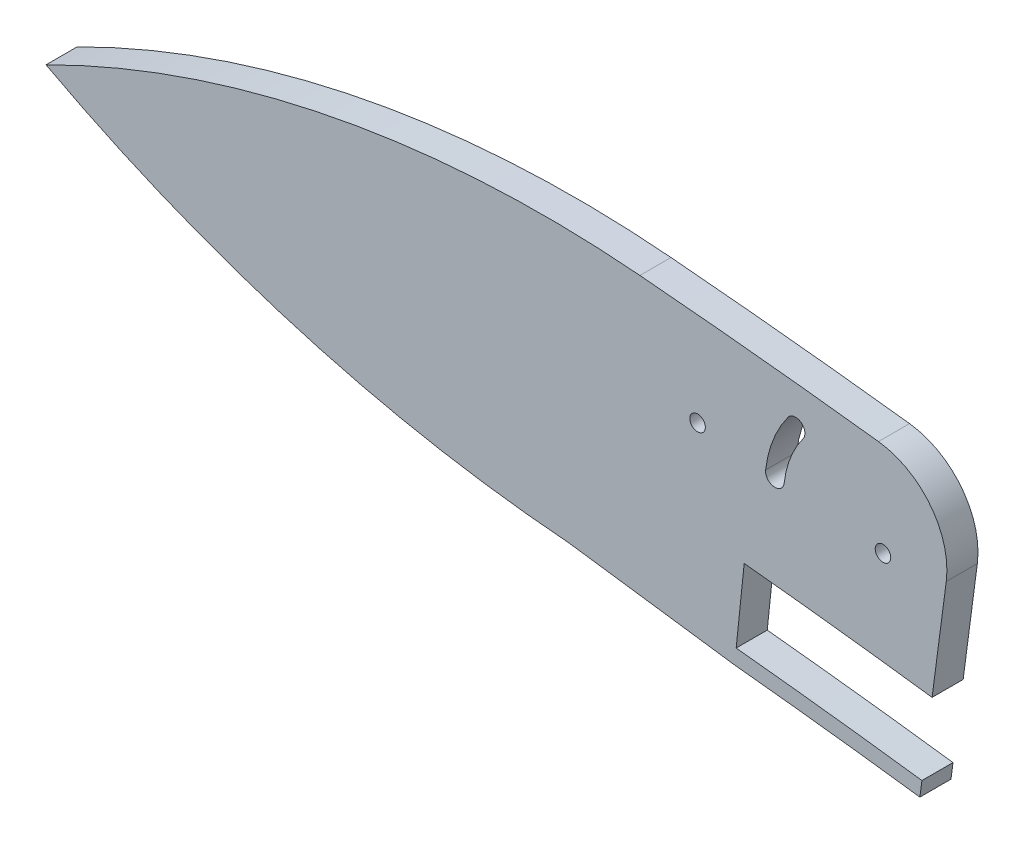
SolidWorks part; units mm, degrees
ref_plane "Přední rovina" through (0, 0, 0) normal (0, 0, 1) x (1, 0, 0)
ref_plane "Horní rovina" through (0, 0, 0) normal (0, 1, 0) x (1, 0, 0)
ref_plane "Pravá rovina" through (0, 0, 0) normal (1, 0, 0) x (0, 0, -1)
sketch "Skica1" plane through (0, 0, 0) normal (0, 0, 1) x (1, 0, 0)
  line L0 (59.8665, -4) -> (57.2058, -23.8222) construction
  line L1 (0, 0) -> (0, -20) construction
  arc A0 (0, 0) -> (59.8665, -4) centre (0, -450) cw construction
  arc A1 (0, -20) -> (57.2058, -23.8222) centre (0, -450) cw construction
  dimension "D1" = 450
  dimension "D2" = 20
  dimension "D3" = 60
sketch "Skica2" plane through (0, 0, 0) normal (0, 0, 1) x (1, 0, 0)
  line L0 (0, 0) -> (0, -20) construction
  line L1 (59.8665, -4) -> (57.2058, -23.8222) construction
  line L2 (58.5689, -5.845) -> (56.281, -23.1948)
  arc A2 (59.6004, -5.9822) -> (0, -2) centre (0, -450) ccw
  arc A3 (58.5689, -5.845) -> (38.2052, -3.632) centre (0, -450) ccw
  arc A4 (0, -11) -> (38.2052, -3.632) centre (32.1148, -74.7883) cw
  arc A5 (57.2723, -23.3267) -> (0, -19.5) centre (0, -450) ccw
  arc A6 (56.281, -23.1948) -> (33.6115, -20.8141) centre (0, -450) ccw
  arc A7 (33.6115, -20.8141) -> (0, -11) centre (40.2963, 64.5435) cw
  dimension "D3" = 11
  dimension "D4" = 1
  dimension "D1" = 2
  dimension "D2" = 0.5
extrude "Přidat vysunutím1" add sketch "Skica2" along normal mid plane 2
sketch "Skica3" plane through (0, 0, 1) normal (0, 0, 1) x (1, 0, 0)
  line L0 (59.8665, -4) -> (57.2058, -23.8222) construction
  arc A0 (53.8429, -11.2917) -> (41.9135, -9.9918) centre (0, -450) ccw construction
  arc A1 (59.8665, -4) -> (0, 0) centre (0, -450) ccw construction
  circle A2 centre (41.9135, -9.9918) radius 0.5
  circle A3 centre (53.8429, -11.2917) radius 0.5
  arc A4 (46.8885, -10.4941) -> (48.2191, -7.1237) centre (53.8429, -11.2917) cw construction
  arc A5 (47.737, -6.7665) -> (46.2924, -10.4257) centre (53.8429, -11.2917) ccw
  arc A6 (48.7011, -7.481) -> (47.4846, -10.5624) centre (53.8429, -11.2917) ccw
  arc A7 (48.7011, -7.481) -> (47.737, -6.7665) centre (48.2191, -7.1237) ccw
  arc A8 (46.2924, -10.4257) -> (47.4846, -10.5624) centre (46.8885, -10.4941) ccw
  point P10 (47.3319, -8.7213)
  dimension "D1" = 8
  dimension "D2" = 1
  dimension "D3" = 1
  dimension "D4" = 12
  dimension "D5" = 1.2
  dimension "D6" = 30
  dimension "D8" = 5
  dimension "D7" = 7
extrude "Odebrat vysunutím1" cut sketch "Skica3" against normal through all
sketch "Skica4" plane through (0, 0, 1) normal (0, 0, 1) x (1, 0, 0)
  line L0 (56.281, -23.1948) -> (58.5689, -5.845) construction
  line L1 (44.3467, -21.7902) -> (44.9133, -16.3195)
  arc A1 (57.0001, -17.742) -> (44.9133, -16.3195) centre (0, -450) ccw
  arc A2 (57.2058, -23.8222) -> (0, -20) centre (0, -450) ccw construction
  arc A3 (56.281, -23.1948) -> (33.6115, -20.8141) centre (0, -450) ccw construction
  dimension "D1" = 6
  dimension "D3" = 13
extrude "Odebrat vysunutím2" cut sketch "Skica4" against normal through all and the other way through all
sketch "Skica5" plane through (0, 0, 0) normal (0, 0, 1) x (1, 0, 0)
  line L0 (33.6115, -20.8141) -> (44.2952, -22.2876)
  line L1 (44.3982, -21.2929) -> (44.3467, -21.7902)
  line L2 (44.9133, -16.3195) -> (44.3467, -21.7902) construction
  line L3 (56.3464, -22.6991) -> (56.2157, -23.6905)
  line L6 (57.0001, -17.742) -> (58.5689, -5.845) construction
  arc A0 (57.2058, -23.8222) -> (0, -20) centre (0, -450) ccw construction
  arc A1 (56.2157, -23.6905) -> (44.2952, -22.2876) centre (0, -450) ccw
  arc A2 (56.3464, -22.6991) -> (44.3982, -21.2929) centre (0, -450) ccw
  arc A3 (57.3388, -22.8311) -> (0, -19) centre (0, -450) ccw construction
  arc A4 (57.2058, -23.8222) -> (0, -20) centre (0, -450) ccw construction
  arc A5 (44.3467, -21.7902) -> (33.6115, -20.8141) centre (0, -450) ccw construction
  arc A6 (44.3467, -21.7902) -> (33.6115, -20.8141) centre (0, -450) ccw
  dimension "D1" = 1
extrude "Přidat vysunutím2" add sketch "Skica5" along normal up to surface and the other way up to surface up to face at (42.4135, -9.9918, 1) other way up to face at (42.4135, -9.9918, -1)
fillet "Zaoblit1" radius 5 1 edges at (58.5689, -5.845, 0)
